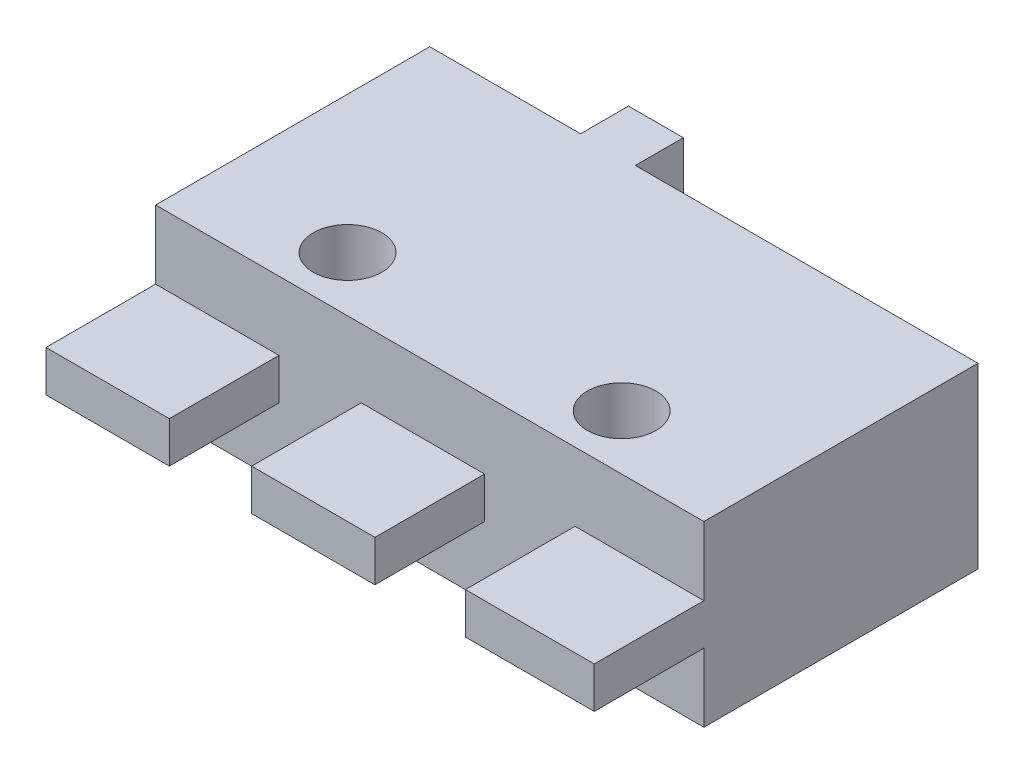
SolidWorks part; units mm, degrees
ref_plane "Front" through (0, 0, 0) normal (0, 0, 1) x (1, 0, 0)
ref_plane "Top" through (0, 0, 0) normal (0, 1, 0) x (1, 0, 0)
ref_plane "Right" through (0, 0, 0) normal (1, 0, 0) x (0, 0, -1)
sketch "Sketch1" plane through (0, 0, 0) normal (0, 1, 0) x (1, 0, 0)
  line L1 (-10, -5) -> (10, -5)
  line L2 (-10, -5) -> (-10, 5)
  line L3 (-10, 5) -> (10, 5)
  line L4 (10, -5) -> (10, 5)
  line L5 (-10, -5) -> (10, 5) construction
  line L6 (-10, 5) -> (10, -5) construction
  point P0 (0, 0)
  dimension "D1" = 20
  dimension "D2" = 10
extrude "Boss-Extrude1" add sketch "Sketch1" along normal blind 6.5
sketch "Sketch2" plane through (0, 0, 5) normal (0, 0, 1) x (1, 0, 0)
  line L0 (0, 0) -> (0, 6.5) construction
  line L1 (-10, 0) -> (10, 0) construction
  line L2 (-10, 6.5) -> (10, 6.5) construction
  line L3 (10, 6.5) -> (10, 0) construction
  line L4 (-10, 2.5) -> (10, 2.5)
  line L5 (-10, 2.5) -> (-10, 4)
  line L6 (-10, 4) -> (10, 4)
  line L7 (10, 2.5) -> (10, 4)
  line L8 (-10, 2.5) -> (10, 4) construction
  line L9 (-10, 4) -> (10, 2.5) construction
  point P6 (0, 3.25)
  dimension "D1" = 1.5
extrude "Boss-Extrude2" add sketch "Sketch2" along normal blind 4
sketch "Sketch3" plane through (0, 6.5, 0) normal (0, 1, 0) x (1, 0, 0)
  line L0 (0, 0) -> (0, -5) construction
  line L1 (-10, -5) -> (10, -5) construction
  circle A0 centre (-5, -3) radius 1.25
  circle A1 centre (5, -3) radius 1.25
  dimension "D2" = 2.5
  dimension "D1" = 5
  dimension "D3" = 2
extrude "Cut-Extrude1" cut sketch "Sketch3" against normal through all
sketch "Sketch4" plane through (0, 0, -5) normal (0, 0, -1) x (-1, 0, 0)
  line L0 (-10, 6.5) -> (10, 6.5) construction
  line L1 (4.5, 0) -> (2.5, 0)
  line L2 (4.5, 0) -> (4.5, 6.5)
  line L3 (4.5, 6.5) -> (2.5, 6.5)
  line L4 (2.5, 0) -> (2.5, 6.5)
  line L5 (4.5, 0) -> (2.5, 6.5) construction
  line L6 (4.5, 6.5) -> (2.5, 0) construction
  line L7 (-10, 0) -> (10, 0) construction
  line L8 (10, 6.5) -> (10, 0) construction
  point P0 (3.5, 3.25)
  dimension "D1" = 2
  dimension "D2" = 6.5
extrude "Boss-Extrude3" add sketch "Sketch4" along normal blind 1.75
sketch "Sketch5" plane through (0, 4, 0) normal (0, 1, 0) x (1, 0, 0)
  line L0 (10, -9) -> (-10, -9) construction
  line L1 (-10, -5) -> (-5.5, -5)
  line L2 (-10, -5) -> (-10, -9)
  line L3 (-10, -9) -> (-5.5, -9)
  line L4 (-5.5, -5) -> (-5.5, -9)
  line L6 (-5.5, -5) -> (-2.5, -5)
  line L7 (-5.5, -5) -> (-5.5, -9)
  line L8 (-5.5, -9) -> (-2.5, -9)
  line L9 (-2.5, -5) -> (-2.5, -9)
  line L11 (-2.5, -5) -> (2, -5)
  line L12 (-2.5, -5) -> (-2.5, -9)
  line L13 (-2.5, -9) -> (2, -9)
  line L14 (2, -5) -> (2, -9)
  line L15 (2, -5) -> (5.3, -5)
  line L16 (2, -5) -> (2, -9)
  line L17 (2, -9) -> (5.3, -9)
  line L18 (5.3, -5) -> (5.3, -9)
  line L19 (5.3, -5) -> (10, -5)
  line L20 (5.3, -5) -> (5.3, -9)
  line L21 (5.3, -9) -> (10, -9)
  line L22 (10, -5) -> (10, -9)
  line M7 (10, -5) -> (-10, -5)
  line M9 (-10, -9) -> (10, -9)
  dimension "D1" = 4.5
  dimension "D2" = 3
  dimension "D3" = 4.5
  dimension "D4" = 3.3
extrude "Cut-Extrude2" cut sketch "Sketch5" against normal blind 1.75 contours L9 L4 M7 M9 | L18 L14 M7 M9
